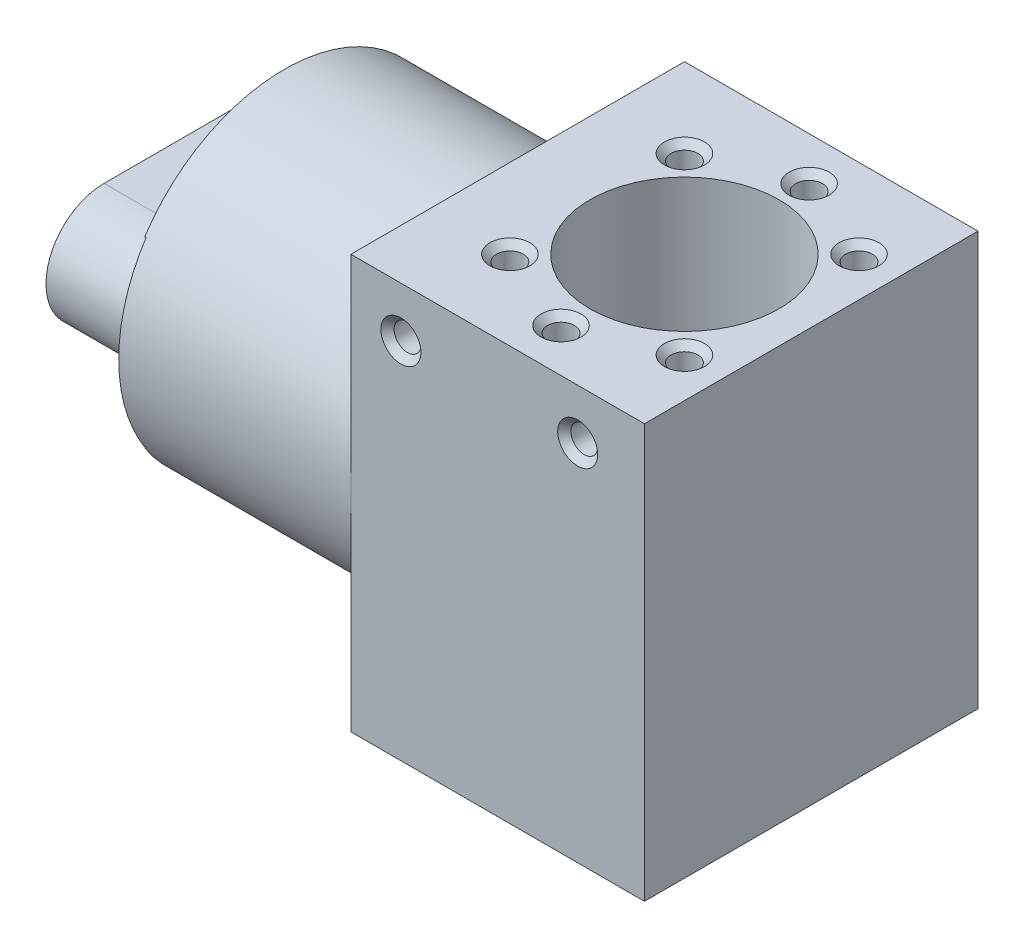
SolidWorks part; units mm, degrees
material "7075-T6 (SN)"
ref_plane "Front Plane" through (0, 0, 0) normal (0, 0, 1) x (1, 0, 0)
ref_plane "Top Plane" through (0, 0, 0) normal (0, 1, 0) x (1, 0, 0)
ref_plane "Right Plane" through (0, 0, 0) normal (1, 0, 0) x (0, 0, -1)
sketch "Sketch3" plane through (0, 0, 0) normal (0, 1, 0) x (1, 0, 0)
  line L1 (0, 31.75) -> (100.33, 31.75)
  line L2 (0, 31.75) -> (0, -31.75)
  line L3 (0, -31.75) -> (100.33, -31.75)
  line L4 (100.33, 31.75) -> (100.33, -31.75)
  point P4 (0, 0)
  dimension "D1" = 63.5
  dimension "D2" = 100.33
extrude "Boss-Extrude3" add sketch "Sketch3" along normal mid plane 78.74
sketch "Sketch5" plane through (0, 0, 0) normal (-1, 0, 0) x (0, 0, 1)
  circle A0 centre (0, 0) radius 31.75
  dimension "D1" = 63.5
extrude "Cut-Extrude1" cut sketch "Sketch5" against normal blind 44.45 flip side to cut
sketch "Sketch6" plane through (0, 39.37, 0) normal (0, 1, 0) x (1, 0, 0)
  line L0 (100.33, -31.75) -> (100.33, 31.75) construction
  circle A0 centre (76.2, 0) radius 18
  dimension "D2" = 36
  dimension "D1" = 24.13
extrude "Cut-Extrude2" cut sketch "Sketch6" against normal through all
sketch "Sketch9" plane through (0, 0, 0) normal (-1, 0, 0) x (0, 0, 1)
  line L0 (-15.24, 0) -> (15.24, 0) construction
  line L1 (-15.24, 11.05) -> (15.24, 11.05)
  line L2 (-15.24, -11.05) -> (15.24, -11.05)
  arc A0 (-15.24, 11.05) -> (-15.24, -11.05) centre (-15.24, 0) ccw
  arc A1 (15.24, -11.05) -> (15.24, 11.05) centre (15.24, 0) ccw
  point P3 (0, 0)
  dimension "D1" = 30.48
  dimension "D2" = 22.1
extrude "Boss-Extrude4" add sketch "Sketch9" along normal blind 19.05
sketch "Sketch12" plane through (0, 0, 0) normal (-1, 0, 0) x (0, 0, 1)
  line L0 (31.75, -39.37) -> (31.75, 0) construction
  line L1 (-31.75, 17.4) -> (31.75, 17.4)
  line L2 (-31.75, 17.4) -> (-31.75, -17.4)
  line L3 (-31.75, -17.4) -> (31.75, -17.4)
  line L4 (31.75, 17.4) -> (31.75, -17.4)
  line L5 (-31.75, 17.4) -> (31.75, -17.4) construction
  line L6 (-31.75, -17.4) -> (31.75, 17.4) construction
  line L7 (-15.24, -11.05) -> (15.24, -11.05) construction
  line L8 (-15.24, -11.05) -> (15.24, -11.05)
  line L9 (15.24, 11.05) -> (-15.24, 11.05) construction
  line L10 (15.24, 11.05) -> (-15.24, 11.05)
  arc A0 (-15.24, 11.05) -> (-15.24, -11.05) centre (-15.24, 0) ccw construction
  arc A1 (15.24, -11.05) -> (15.24, 11.05) centre (15.24, 0) ccw construction
  arc A2 (-15.24, 11.05) -> (-15.24, -11.05) centre (-15.24, 0) ccw
  arc A3 (15.24, -11.05) -> (15.24, 11.05) centre (15.24, 0) ccw
  point P0 (0, 0)
  dimension "D1" = 6.35
extrude "Cut-Extrude3" cut sketch "Sketch12" against normal blind 0.254
hole_wizard "5/16-18 Tapped Hole1" positions "Sketch11" profile "Sketch10" tap size "5/16-18" standard "ANSI Inch"
sketch "Sketch11" plane through (-19.05, 0, 0) normal (-1, 0, 0) x (0, 0, 1)
  point P5 (-15.24, 0)
  point P8 (15.24, 0)
sketch "Sketch10" plane through (-19.05, 0, -15.24) normal (0, 1, 0) x (0, 0, 1)
  line L0 (0, 0) -> (0, 22.0779)
  line L1 (0, 22.0779) -> (3.2639, 20.1168)
  line L2 (3.2639, 20.1168) -> (3.2639, 1.3398)
  line L3 (3.2639, 1.3398) -> (4.6037, 0)
  line L5 (4.6037, 0) -> (0, 0)
  line L6 (-3.2639, 1.3398) -> (-4.6037, 0) construction
  line L10 (0, 22.0779) -> (-3.2639, 20.1168) construction
  line L11 (0, -6.35) -> (0, 107.95) construction
  dimension "Tap Drill Dia." = 6.5278
  dimension "Tap Drill Depth" = 20.1168
  dimension "Near C'Sink Dia." = 9.2075
  dimension "Near C'Sink Angle" = 90
  dimension "Drill Angle" = 118
cosmetic thread "Hole Thread7" parameters "D1"=15.875, "D2"=7.9375
cosmetic thread "Hole Thread8" parameters "D1"=15.875, "D2"=7.9375
hole_wizard "1/4-20 Tapped Hole2" positions "Sketch8" profile "Sketch7" tap size "1/4-20" standard "ANSI Inch"
sketch "Sketch8" plane through (0, 39.37, 0) normal (0, 1, 0) x (1, 0, 0)
  line L3 (59.583, -16.617) -> (92.817, 16.617) construction
  line L5 (59.583, 16.617) -> (92.817, -16.617) construction
  line L9 (76.2, -23.5) -> (76.2, 23.5) construction
  circle A1 centre (76.2, 0) radius 23.5 construction
  point P7 (76.432, 23.4989)
  point P21 (59.583, -16.617)
  point P22 (92.817, 16.617)
  point P26 (59.583, 16.617)
  point P27 (92.817, -16.617)
  point P33 (76.2, -23.5)
  dimension "D1" = 47
  dimension "D2" = 45
  dimension "D3" = 45
sketch "Sketch7" plane through (76.432, 39.37, -23.4989) normal (1, 0, 0) x (0, 0, 1)
  line L0 (0, 0) -> (0, 18.0438)
  line L1 (0, 18.0438) -> (2.5527, 16.51)
  line L2 (2.5527, 16.51) -> (2.5527, 1.2573)
  line L3 (2.5527, 1.2573) -> (3.81, 0)
  line L5 (3.81, 0) -> (0, 0)
  line L6 (-2.5527, 1.2573) -> (-3.81, 0) construction
  line L10 (0, 18.0438) -> (-2.5527, 16.51) construction
  line L11 (0, -6.35) -> (0, 107.95) construction
  dimension "Tap Drill Dia." = 5.1054
  dimension "Tap Drill Depth" = 16.51
  dimension "Near C'Sink Dia." = 7.62
  dimension "Near C'Sink Angle" = 90
  dimension "Drill Angle" = 118
cosmetic thread "Hole Thread1" parameters "D1"=12.7, "D2"=6.35
cosmetic thread "Hole Thread2" parameters "D1"=12.7, "D2"=6.35
cosmetic thread "Hole Thread3" parameters "D1"=12.7, "D2"=6.35
cosmetic thread "Hole Thread4" parameters "D1"=12.7, "D2"=6.35
cosmetic thread "Hole Thread5" parameters "D1"=12.7, "D2"=6.35
cosmetic thread "Hole Thread6" parameters "D1"=12.7, "D2"=6.35
mirror "Mirror1" about plane through (0, 0, 0) normal (0, 1, 0) of "1/4-20 Tapped Hole2"
hole_wizard "1/4-20 Tapped Hole3" positions "Sketch14" profile "Sketch13" tap size "1/4-20" standard "ANSI Inch"
sketch "Sketch14" plane through (0, 0, 31.75) normal (0, 0, 1) x (1, 0, 0)
  line L0 (44.45, 0) -> (44.45, 39.37) construction
  line L1 (44.45, 39.37) -> (100.33, 39.37) construction
  line L2 (53.975, 29.845) -> (87.63, 29.845) construction
  line L4 (100.33, 39.37) -> (100.33, -39.37) construction
  point P0 (53.975, 29.845)
  point P8 (87.63, 29.845)
  dimension "D1" = 9.525
  dimension "D2" = 9.525
  dimension "D3" = 12.7
cosmetic thread "Hole Thread10" parameters "D1"=12.7, "D2"=6.35
sketch "Sketch13" plane through (53.975, 29.845, 31.75) normal (1, 0, 0) x (0, -1, 0)
  line L0 (0, 0) -> (0, 18.0438)
  line L1 (0, 18.0438) -> (2.5527, 16.51)
  line L2 (2.5527, 16.51) -> (2.5527, 1.2573)
  line L3 (2.5527, 1.2573) -> (3.81, 0)
  line L5 (3.81, 0) -> (0, 0)
  line L6 (-2.5527, 1.2573) -> (-3.81, 0) construction
  line L10 (0, 18.0438) -> (-2.5527, 16.51) construction
  line L11 (0, -6.35) -> (0, 107.95) construction
  dimension "Tap Drill Dia." = 5.1054
  dimension "Tap Drill Depth" = 16.51
  dimension "Near C'Sink Dia." = 7.62
  dimension "Near C'Sink Angle" = 90
  dimension "Drill Angle" = 118
cosmetic thread "Hole Thread11" parameters "D1"=12.7, "D2"=6.35
mirror "Mirror2" about plane through (0, 0, 0) normal (0, 0, 1) of "1/4-20 Tapped Hole3"
